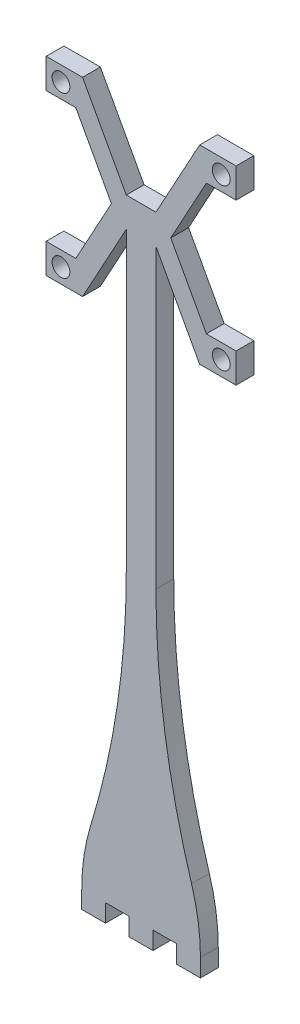
SolidWorks part; units mm, degrees
ref_plane "Front Plane" through (0, 0, 0) normal (0, 0, 1) x (1, 0, 0)
ref_plane "Top Plane" through (0, 0, 0) normal (0, 1, 0) x (1, 0, 0)
ref_plane "Right Plane" through (0, 0, 0) normal (1, 0, 0) x (0, 0, -1)
sketch "Sketch1" plane through (0, 0, 0) normal (0, 0, 1) x (1, 0, 0)
  line L0 (-10, 0) -> (-10, 3)
  line L1 (-10, 0) -> (-6, 0)
  line L2 (-6, 0) -> (-6, 3)
  line L3 (-6, 3) -> (-2, 3)
  line L4 (-2, 3) -> (-2, 0)
  line L5 (-2, 0) -> (2, 0)
  line L6 (2, 0) -> (2, 3)
  line L7 (2, 3) -> (6, 3)
  line L8 (6, 3) -> (6, 0)
  line L9 (6, 0) -> (10, 0)
  line L10 (10, 0) -> (10, 3)
  line L11 (-9.8636, 89.5) -> (-16, 89.5)
  line L12 (-16, 89.5) -> (-16, 94.5)
  line L13 (-16, 121.5) -> (-9.8636, 121.5)
  line L14 (16, 121.5) -> (16, 116.5)
  line L15 (16, 89.5) -> (9.8636, 89.5)
  line L16 (-16, 116.5) -> (-11, 116.5)
  line L17 (16, 94.5) -> (16, 89.5)
  line L18 (-11, 116.5) -> (-5, 105.5)
  line L19 (-11, 94.5) -> (-16, 94.5)
  line L20 (-16, 116.5) -> (-16, 121.5)
  line L21 (0, 167.4726) -> (0, 43.5274) construction
  line L22 (11, 94.5) -> (16, 94.5)
  line L23 (-5, 105.5) -> (-11, 94.5)
  line L24 (5, 105.5) -> (11, 94.5)
  line L25 (16, 116.5) -> (11, 116.5)
  line L26 (11, 116.5) -> (5, 105.5)
  line L27 (2.5, 108) -> (-2.5, 108)
  line L28 (-2.5, 108) -> (-9.8636, 121.5)
  line L29 (0, 105.5) -> (-123.314, 105.5) construction
  line L31 (-2.5, 103) -> (-9.8636, 89.5)
  line L32 (2.5, 108) -> (9.8636, 121.5)
  line L33 (2.5, 103) -> (9.8636, 89.5)
  line L34 (9.8636, 121.5) -> (16, 121.5)
  line L35 (-2.5, 103) -> (-2.5, 53)
  line L37 (2.5, 103) -> (2.5, 53)
  arc A0 (-10, 3) -> (-8.5, 13) centre (24.0833, 3) cw
  arc A1 (-8.5, 13) -> (-2.5, 53) centre (-138.8333, 53) ccw
  arc A2 (8.5, 13) -> (2.5, 53) centre (138.8333, 53) cw
  arc A3 (10, 3) -> (8.5, 13) centre (-24.0833, 3) ccw
  circle A4 centre (-13.5, 92) radius 1.5
  circle A5 centre (13.5, 92) radius 1.5
  circle A6 centre (13.5, 119) radius 1.5
  circle A7 centre (-13.5, 119) radius 1.5
  point P18 (0, 0)
  point P34 (0, 105.5)
  point P42 (0, 108)
  point P44 (0, 103)
  dimension "D14" = 3
  dimension "D1" = 4
  dimension "D2" = 3
  dimension "D3" = 32
  dimension "D4" = 32
  dimension "D5" = 5
  dimension "D7" = 5
  dimension "D8" = 50
  dimension "D9" = 10
  dimension "D10" = 2.5
  dimension "D11" = 2.5
  dimension "D12" = 50
  dimension "D13" = 10
  dimension "D15" = 2.5
  dimension "D16" = 2.5
extrude "Boss-Extrude1" add sketch "Sketch1" along normal blind 3
